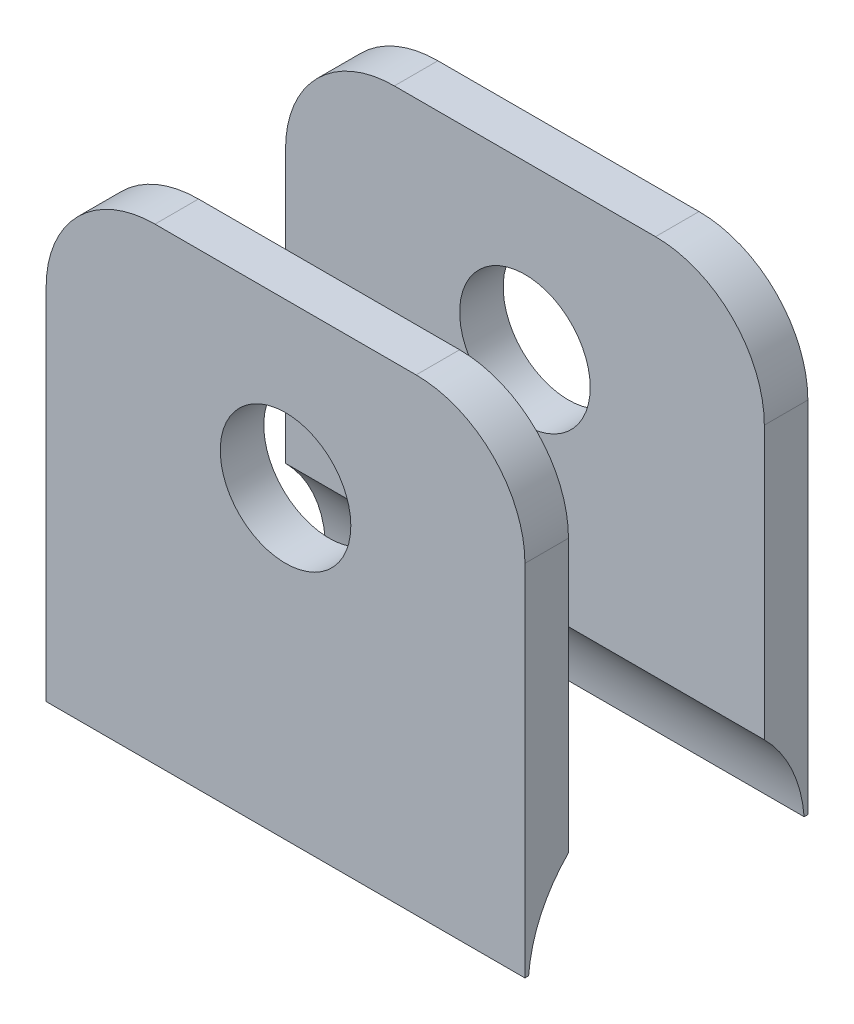
SolidWorks part; units mm, degrees
ref_plane "Front Plane" through (0, 0, 0) normal (0, 0, 1) x (1, 0, 0)
ref_plane "Top Plane" through (0, 0, 0) normal (0, 1, 0) x (1, 0, 0)
ref_plane "Right Plane" through (0, 0, 0) normal (1, 0, 0) x (0, 0, -1)
sketch3d "3DSketch1" plane through (0, 0, 0) normal (0, 0, 1) x (1, 0, 0)
  dimension "D1" = 9
sketch "Sketch2" plane through (0, 0, 9) normal (0, 0, 1) x (1, 0, 0)
  line L0 (-22, 0) -> (22, 0) construction
  line L1 (0, 0) -> (0, 15) construction
  line L2 (-22, 0) -> (-22, 15)
  line L3 (-22, 15) -> (22, 15)
  line L4 (22, 15) -> (22, -28)
  line L5 (22, -28) -> (-22, -28)
  line L6 (-22, -28) -> (-22, 0)
  circle A0 centre (0, 0) radius 6
  point P4 (0, 0)
  dimension "D1" = 12
  dimension "D2" = 15
  dimension "D3" = 28
  dimension "D4" = 44
extrude "Boss-Extrude1" add sketch "Sketch2" along normal blind 4
fillet "Fillet1" radius 10 2 edges at (22, 15, 11) (-22, 15, 11)
mirror "Mirror2" about plane through (0, 0, 0) normal (0, 0, 1) of bodies 101
sketch "Sketch3" plane through (0, 0, 0) normal (1, 0, 0) x (0, 0, -1)
  line L0 (-13, -28) -> (13, -28) construction
  line L1 (0, 0) -> (0, -29) construction
  circle A0 centre (0, -29) radius 12.7
  point P8 (0, -20.4538)
  point P10 (0, -24)
  point P11 (0, -24)
  point P12 (0, -28.6605)
  point P13 (0, -27)
  dimension "D1" = 25.4
  dimension "D2" = 29
extrude "Cut-Extrude1" cut sketch "Sketch3" against normal blind 25 and the other way blind 25
